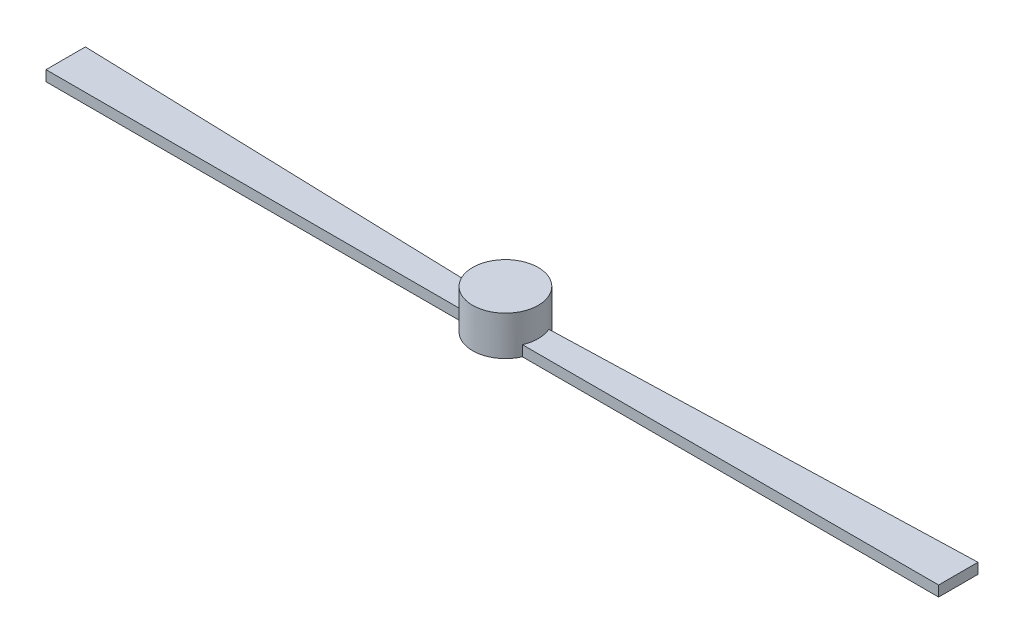
SolidWorks part; units mm, degrees
ref_plane "Front Plane" through (0, 0, 0) normal (0, 0, 1) x (1, 0, 0)
ref_plane "Top Plane" through (0, 0, 0) normal (0, 1, 0) x (1, 0, 0)
ref_plane "Right Plane" through (0, 0, 0) normal (1, 0, 0) x (0, 0, -1)
other "Graphic1"
other "Graphic (Closed) -1"
other "Graphic (Closed) -2"
other "Graphic (Closed) -3"
other "Graphic (Open) -1"
other "Graphic (Open) -2"
other "Graphic (Open) -3"
other "Graphic (Open) -4"
other "Graphic (Open) -5"
other "Graphic (Open) -6"
other "Graphic (Closed) -4"
other "Graphic (Closed) -5"
other "Graphic (Closed) -6"
other "Graphic (Closed) -7"
other "Graphic (Closed) -8"
other "Graphic (Closed) -9"
other "Graphic (Closed) -10"
other "Graphic (Closed) -11"
other "Graphic (Closed) -12"
other "Graphic (Closed) -13"
other "Graphic (Closed) -14"
other "Graphic (Closed) -15"
other "Graphic (Closed) -16"
other "Graphic (Closed) -17"
other "Graphic (Closed) -18"
other "Graphic (Closed) -19"
other "Graphic (Closed) -20"
other "Graphic (Closed) -21"
sketch "Sketch1" plane through (0, 0, 0) normal (0, 1, 0) x (1, 0, 0)
  circle A0 centre (0, 0) radius 25
extrude "Boss-Extrude1" add sketch "Sketch1" along normal blind 30
sketch "Sketch2" plane through (0, 0, 0) normal (0, 1, 0) x (1, 0, 0)
  line L0 (15, 10) -> (340, 20)
  line L1 (340, 20) -> (340, -10)
  line L2 (340, -10) -> (15, -10)
  line L3 (15, -10) -> (15, 10)
  line L4 (-15, 10) -> (-340, 20)
  line L5 (-340, 20) -> (-340, -10)
  line L6 (-340, -10) -> (-15, -10)
  line L7 (-15, -10) -> (-15, 10)
extrude "Boss-Extrude2" add sketch "Sketch2" along normal blind 8
